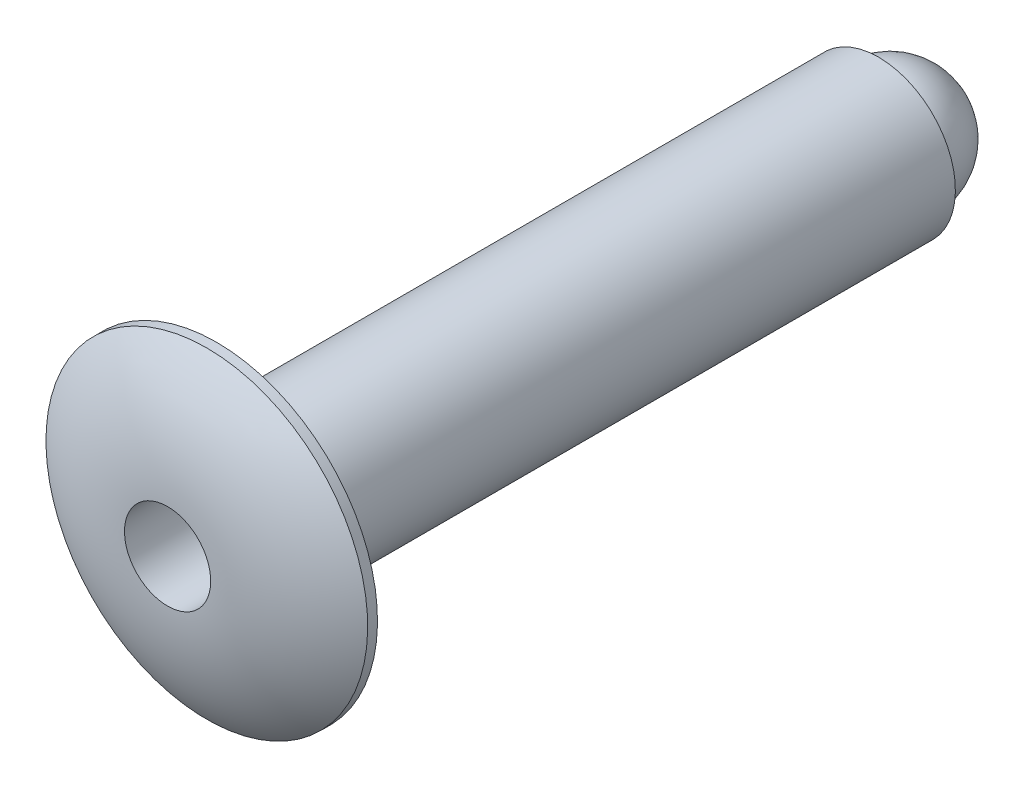
SolidWorks part; units mm, degrees
ref_plane "Front" through (0, 0, 0) normal (0, 0, 1) x (1, 0, 0)
ref_plane "Top" through (0, 0, 0) normal (0, 1, 0) x (1, 0, 0)
ref_plane "Right" through (0, 0, 0) normal (1, 0, 0) x (0, 0, -1)
sketch "Sketch1" plane through (0, 0, 0) normal (1, 0, 0) x (0, 0, -1)
  line L0 (-26.9875, 0) -> (-1.27, 0) construction
  line L1 (-1.27, 0) -> (0, 0) construction
  line L2 (0, 0) -> (17.145, 0) construction
  line L3 (17.145, 0) -> (19.05, 0) construction
  line L8 (0, 4.1656) -> (0, -4.1656) construction
  line L9 (17.145, 1.9844) -> (17.145, -1.9844) construction
  dimension "Length" = 17.145
  dimension "Head Height" = 1.27
  dimension "D5" = 1.905
  dimension "D9" = 25.7175
  dimension "Diameter" = 3.9688
  dimension "Head Diameter" = 8.3312
sketch "Sketch2" plane through (0, 0, 0) normal (1, 0, 0) x (0, 0, -1)
  line L0 (-26.9875, 0.9922) -> (-26.9875, 0) construction
  line L1 (-26.9875, 0.9922) -> (0, 0.9922) construction
  line L2 (0, 4.1656) -> (0, -4.1656) construction
  line L3 (0, 0) -> (0, 4.1656) construction
  line L4 (-1.27, 0) -> (-1.27, -1.8472) construction
  line L5 (17.145, 1.9844) -> (0, 1.9844)
  line L6 (17.145, 1.9844) -> (17.145, 0) construction
  line L7 (19.05, 0) -> (19.05, 1.9844) construction
  line L8 (17.145, 1.9844) -> (17.145, 0)
  line L9 (19.05, 1.9844) -> (17.145, 1.9844) construction
  line L11 (17.145, 0) -> (19.05, 0) construction
  line L12 (17.145, 0) -> (1.7145, 0)
  line L13 (-1.27, 0.9922) -> (-1.27, 0) construction
  line L14 (17.145, 1.9844) -> (17.145, 0) construction
  line L15 (17.145, 1.9844) -> (17.145, 0) construction
  line L16 (17.145, 0) -> (17.145, 1.9844) construction
  line L17 (17.145, 1.9844) -> (17.145, 0) construction
  line L18 (17.145, 0) -> (17.145, 1.9844) construction
  line L19 (0, 1.9844) -> (0, 4.1656)
  line L20 (-1.27, 1.1162) -> (0, 1.1162)
  line L21 (-26.9875, 1.1162) -> (0, 1.1162) construction
  line L22 (0, 4.1656) -> (-0.254, 4.1656)
  line L23 (0, 1.1162) -> (1.7145, 1.1162)
  line L24 (1.7145, 1.1162) -> (1.7145, 0)
  arc A0 (19.05, 0) -> (17.145, 1.5875) centre (17.436, 0) ccw construction
  arc A2 (-0.254, 4.1656) -> (-1.27, 1.1162) centre (3.8142, 1.1162) ccw
  dimension "D3" = 0.254
  dimension "D1" = 0.9922
  dimension "D2" = 1.7145
  dimension "D5" = 1.5875
  dimension "D4" = 0.124
revolve "Revolve1" add sketch "Sketch2" angle 360 about L12
sketch "Sketch7" plane through (0, 0, 0) normal (1, 0, 0) x (0, 0, -1)
  line L0 (-26.9875, 0.9922) -> (1.7145, 0.9922)
  line L1 (1.7145, 1.1162) -> (1.7145, 0) construction
  line L2 (1.7145, 0.9922) -> (1.7145, 0)
  line L3 (1.7145, 0) -> (-26.9875, 0)
  line L4 (-26.9875, 0) -> (-26.9875, 0.9922)
revolve "Revolve2" [suppressed] add sketch "Sketch7" angle 360 about L0
sketch "Sketch8" plane through (0, 0, 0) normal (1, 0, 0) x (0, 0, -1)
  line L1 (17.145, 1.5875) -> (17.145, 0)
  line L2 (17.145, 0) -> (19.05, 0)
  arc A0 (19.05, 0) -> (17.145, 1.5875) centre (17.436, 0) ccw construction
  arc A1 (19.05, 0) -> (17.145, 1.5875) centre (17.436, 0) ccw
revolve "Revolve3" add sketch "Sketch8" angle 360 about L3
sketch "Sketch3" [suppressed] plane through (0, 0, 0) normal (0, 1, 0) x (1, 0, 0)
  line L0 (-1.1954, -24.5045) -> (-0.6449, -26.9875)
  line L2 (-0.9922, -26.9875) -> (0.9922, -26.9875) construction
  line L3 (0, -26.9875) -> (0, -27.4955) construction
  line L4 (-0.6449, -26.9875) -> (0.6449, -26.9875)
  line L5 (-1.1954, -24.5045) -> (-1.1954, -27.4955)
  line L6 (-1.1954, -27.4955) -> (1.1954, -27.4955)
  line L7 (1.1954, -27.4955) -> (1.1954, -24.5045)
  line L8 (-0.9922, 1.7145) -> (-0.9922, -26.9875) construction
  line L9 (0, -26.9875) -> (0, -1.27) construction
  line L10 (0.6449, -26.9875) -> (1.1954, -24.5045)
  point P12 (0, -26.9875)
  dimension "D3" = 0.508
  dimension "D2" = 0.2032
  dimension "D1" = 25
  dimension "D4" = 1.2898
extrude "Cut-Extrude1" [suppressed] cut sketch "Sketch3" against normal through all both and the other way through all
pattern_circular "CirPattern1" [suppressed] count 2 every 90 about axis through (0, 0, 26.9875) along (0, 0, -1)
sketch "Sketch9" [suppressed] plane through (0, 0, 26.9875) normal (0, 0, 1) x (1, 0, 0)
  line L8 (-0.6195, -0.6195) -> (0.6195, -0.6195)
  line L9 (0.6195, -0.6195) -> (0.6195, 0.6195)
  line L10 (0.6195, 0.6195) -> (-0.6195, 0.6195)
  line L11 (-0.6195, 0.6195) -> (-0.6195, -0.6195)
  line L12 (-0.6195, -0.6195) -> (0.6195, -0.6195)
  line L13 (0.6195, -0.6195) -> (0.6195, 0.6195)
  line L14 (0.6195, 0.6195) -> (-0.6195, 0.6195)
  line L15 (-0.6195, 0.6195) -> (-0.6195, -0.6195)
  dimension "D1" = 0.0254
extrude "Cut-Extrude3" [suppressed] cut sketch "Sketch9" against normal blind 2.54
fillet "Fillet2" radius 0.254 1 edges at (0, 1.9844, 0)
ref_plane "Contact Plane 1" through (0, 0, 0) normal (0, 0, -1) x (-1, 0, 0)
equation "\"D5@Sketch1\" = \"Head Height@Sketch1\" * 1.5"
equation "\"D9@Sketch1\" = \"Length@Sketch1\" * 1.5"
equation "\"D1@Sketch2\"=\"Diameter@Sketch1\"/4"
equation "\"D4@Sketch2\"=\"D1@Sketch2\"/8"
equation "\"D2@Sketch2\"=\"Length@Sketch1\"/10"
equation "\"D4@Sketch3\"=\"D1@Sketch2\"*2*.65"
equation "\"D5@Sketch2\"=\"Diameter@Sketch1\"*.8/2"
